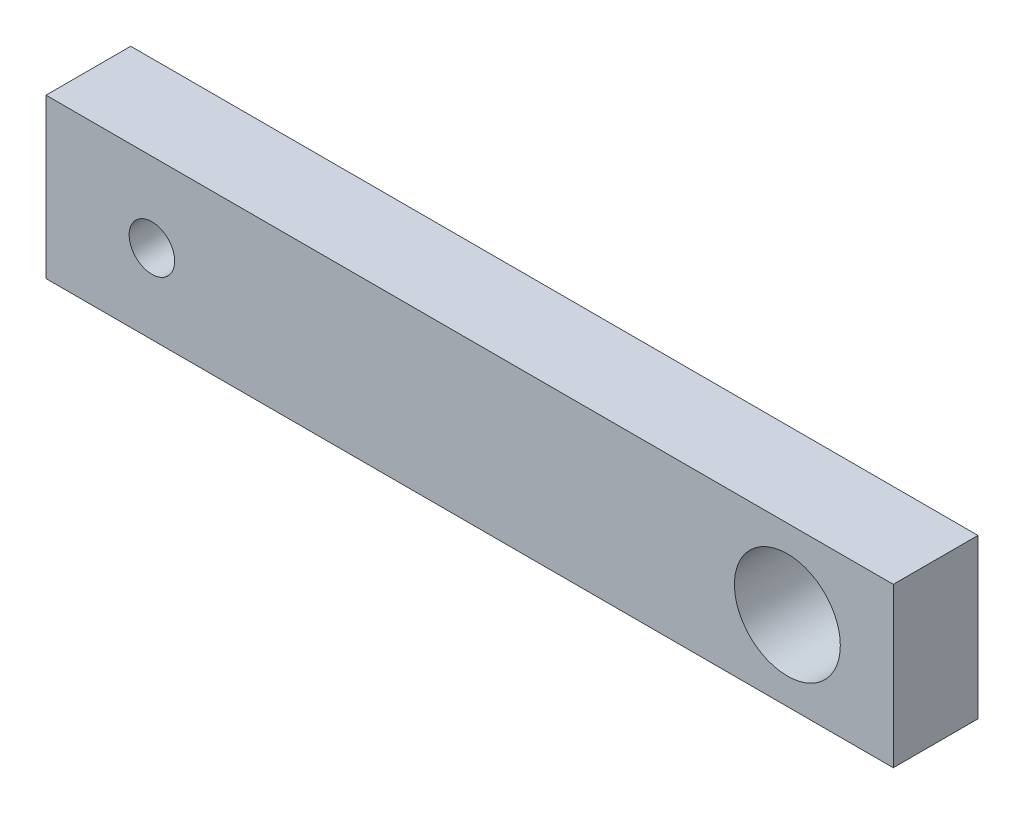
SolidWorks part; units mm, degrees
ref_plane "Front Plane" through (0, 0, 0) normal (0, 0, 1) x (1, 0, 0)
ref_plane "Top Plane" through (0, 0, 0) normal (0, 1, 0) x (1, 0, 0)
ref_plane "Right Plane" through (0, 0, 0) normal (1, 0, 0) x (0, 0, -1)
sketch "Sketch1" plane through (0, 0, 0) normal (0, 0, 1) x (1, 0, 0)
  line L0 (0, -7.5) -> (80, -7.5) construction
  line L1 (0, 0) -> (80, 0)
  line L2 (0, 0) -> (0, -15)
  line L3 (0, -15) -> (80, -15)
  line L4 (80, 0) -> (80, -15)
  circle A0 centre (10, -7.5) radius 2.15
  circle A1 centre (70, -7.5) radius 5
  dimension "D3" = 60
  dimension "D4" = 10
  dimension "D5" = 4.3
  dimension "D6" = 10
  dimension "D1" = 80
  dimension "D2" = 15
extrude "Boss-Extrude1" add sketch "Sketch1" along normal blind 8
